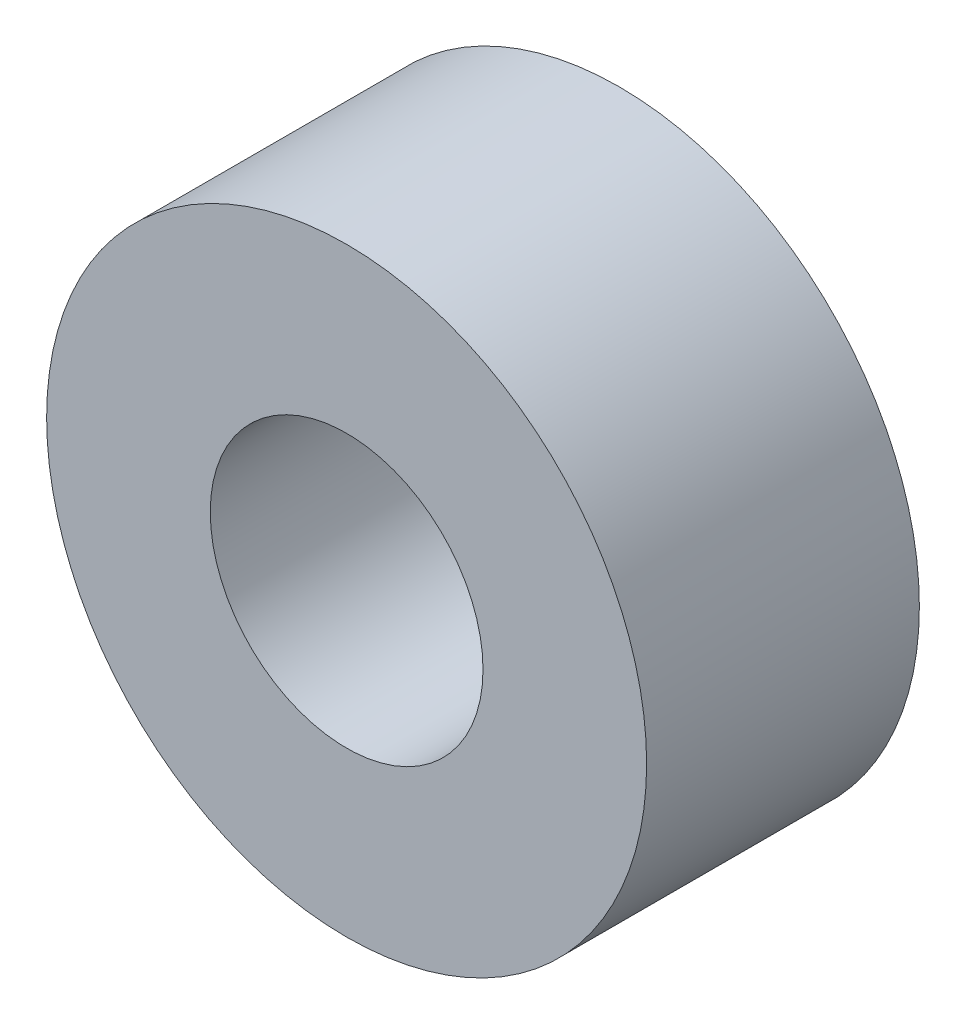
SolidWorks part; units mm, degrees
ref_plane "Front Plane" through (0, 0, 0) normal (0, 0, 1) x (1, 0, 0)
ref_plane "Top Plane" through (0, 0, 0) normal (0, 1, 0) x (1, 0, 0)
ref_plane "Right Plane" through (0, 0, 0) normal (1, 0, 0) x (0, 0, -1)
sketch "Sketch1" plane through (0, 0, 0) normal (0, 0, 1) x (1, 0, 0)
  circle A0 centre (0, 0) radius 5.5
  circle A1 centre (0, 0) radius 2.5
  dimension "D1" = 5
  dimension "D2" = 11
extrude "Boss-Extrude1" add sketch "Sketch1" along normal blind 5
